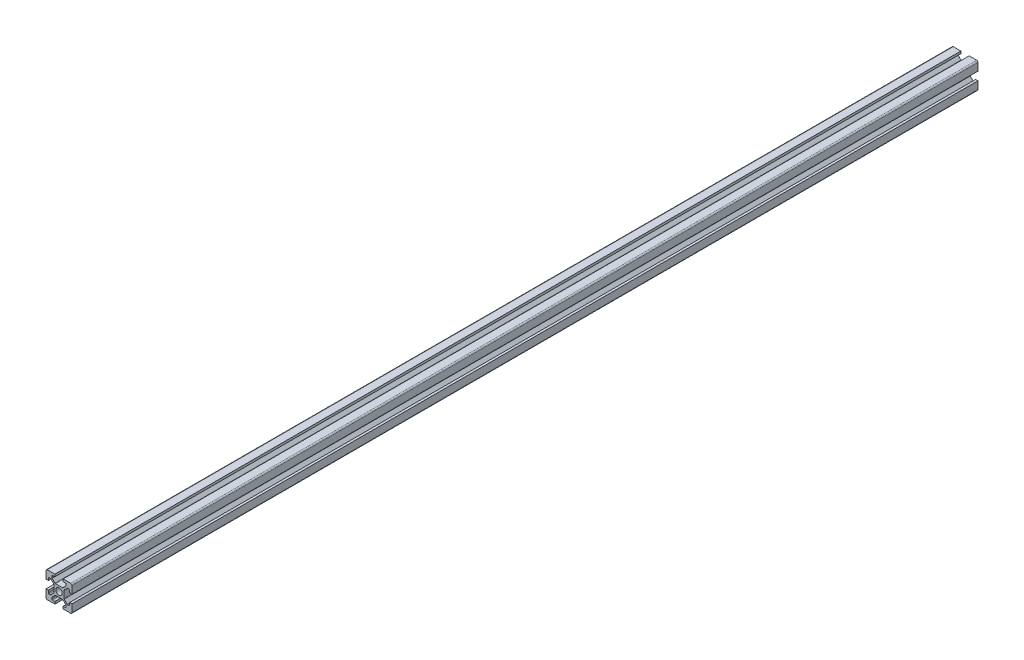
SolidWorks part; units mm, degrees
material "1060 Alloy"
ref_plane "Front Plane" through (0, 0, 0) normal (0, 0, 1) x (1, 0, 0)
ref_plane "Top Plane" through (0, 0, 0) normal (0, 1, 0) x (1, 0, 0)
ref_plane "Right Plane" through (0, 0, 0) normal (1, 0, 0) x (0, 0, -1)
sketch "Sketch1" plane through (0, 0, 0) normal (0, 0, 1) x (1, 0, 0)
  line L0 (20, 0) -> (-8.059, 28.059) construction
  line L1 (0, 0) -> (6.8, 0)
  line L2 (0, 0) -> (0, 6.8)
  line L3 (0, 20) -> (6.8, 20)
  line L4 (20, 0) -> (20, 6.8)
  line L5 (6.8, 20) -> (6.8, 18.2)
  line L6 (20, 20) -> (8.2322, 8.2322) construction
  line L7 (12.95, 6.1) -> (7.05, 6.1)
  line L8 (13.9, 7.05) -> (13.9, 12.95)
  line L9 (12.95, 13.9) -> (7.05, 13.9)
  line L10 (6.1, 7.05) -> (6.1, 12.95)
  line L11 (13.9, 6.1) -> (6.1, 13.9) construction
  line L12 (13.9, 13.9) -> (6.1, 6.1) construction
  line L13 (4.55, 16.4) -> (7.05, 13.9)
  line L14 (13.2, 18.2) -> (13.2, 20)
  line L15 (1.8, 6.8) -> (0, 6.8)
  line L16 (0, 13.2) -> (0, 20)
  line L17 (0, 13.2) -> (1.8, 13.2)
  line L18 (10, 10) -> (10, 13.9) construction
  line L19 (16.4, 4.55) -> (13.9, 7.05)
  line L20 (4.55, 16.4) -> (4.55, 18.2)
  line L21 (4.55, 18.2) -> (6.8, 18.2)
  line L22 (13.2, 18.2) -> (15.45, 18.2)
  line L23 (15.45, 18.2) -> (15.45, 16.4)
  line L24 (15.45, 16.4) -> (12.95, 13.9)
  line L25 (16.4, 4.55) -> (18.2, 4.55)
  line L26 (18.2, 4.55) -> (18.2, 6.8)
  line L27 (20, 6.8) -> (18.2, 6.8)
  line L28 (18.2, 13.2) -> (20, 13.2)
  line L29 (18.2, 13.2) -> (18.2, 15.45)
  line L30 (18.2, 15.45) -> (16.4, 15.45)
  line L31 (16.4, 15.45) -> (13.9, 12.95)
  line L32 (1.8, 4.55) -> (3.6, 4.55)
  line L33 (3.6, 15.45) -> (6.1, 12.95)
  line L34 (3.6, 15.45) -> (1.8, 15.45)
  line L35 (1.8, 15.45) -> (1.8, 13.2)
  line L36 (0, 13.2) -> (1.8, 13.2)
  line L37 (1.8, 6.8) -> (0, 6.8)
  line L38 (3.6, 4.55) -> (6.1, 7.05)
  line L39 (1.8, 6.8) -> (1.8, 4.55)
  line L40 (15.45, 3.6) -> (12.95, 6.1)
  line L41 (4.55, 3.6) -> (7.05, 6.1)
  line L42 (4.55, 1.8) -> (4.55, 3.6)
  line L43 (6.8, 1.8) -> (4.55, 1.8)
  line L44 (6.8, 1.8) -> (6.8, 0)
  line L45 (15.45, 3.6) -> (15.45, 1.8)
  line L46 (15.45, 1.8) -> (13.2, 1.8)
  line L47 (13.2, 0) -> (13.2, 1.8)
  line L48 (13.2, 20) -> (20, 20)
  line L49 (20, 13.2) -> (20, 20)
  line L50 (13.2, 0) -> (20, 0)
  line L51 (6.1, 6.1) -> (-5.5045, -5.5045) construction
  circle A0 centre (10, 10) radius 2.5
  point P25 (10, 16.4)
  point P39 (13.2, 19.1)
  point P46 (0.9, 6.8)
  dimension "D3" = 5
  dimension "D2" = 20
  dimension "D4" = 7.8
  dimension "D5" = 7.8
  dimension "D6" = 6.8
  dimension "D7" = 6.8
  dimension "D8" = 1.8
  dimension "D9" = 10.9
  dimension "D10" = 1.8
  dimension "D11" = 10.9
  dimension "D12" = 20
extrude "Boss-Extrude1" add sketch "Sketch1" along normal blind 697.1 contours L47 L50 L4 L27 L26 L25 L19 L8 L31 L30 L29 L28 L49 L48 L14 L22 L23 L24 L9 L13 L20 L21 L5 L3 L16 L17 L35 L34 L33 L10 L38 L32 L39 L15 L2 L1 L44 L43 L42 L41 L7 L40 L45 L46 A0
fillet "Fillet1" radius 1 4 edges at (20, 20, 348.55) (20, 0, 348.55) (0, 0, 348.55) (0, 20, 348.55)
fillet "Fillet2" radius 0.5 6 edges at (4.55, 18.2, 348.55) (4.55, 16.4, 348.55) (7.05, 13.9, 348.55) (15.45, 18.2, 348.55) (15.45, 16.4, 348.55) (12.95, 13.9, 348.55)
fillet "Fillet3" radius 0.5 6 edges at (18.2, 15.45, 348.55) (16.4, 15.45, 348.55) (13.9, 12.95, 348.55) (18.2, 4.55, 348.55) (13.9, 7.05, 348.55) (16.4, 4.55, 348.55)
fillet "Fillet4" radius 0.5 6 edges at (1.8, 15.45, 348.55) (3.6, 15.45, 348.55) (6.1, 12.95, 348.55) (3.6, 4.55, 348.55) (1.8, 4.55, 348.55) (6.1, 7.05, 348.55)
fillet "Fillet5" radius 0.5 6 edges at (7.05, 6.1, 348.55) (4.55, 3.6, 348.55) (4.55, 1.8, 348.55) (15.45, 1.8, 348.55) (15.45, 3.6, 348.55) (12.95, 6.1, 348.55)
